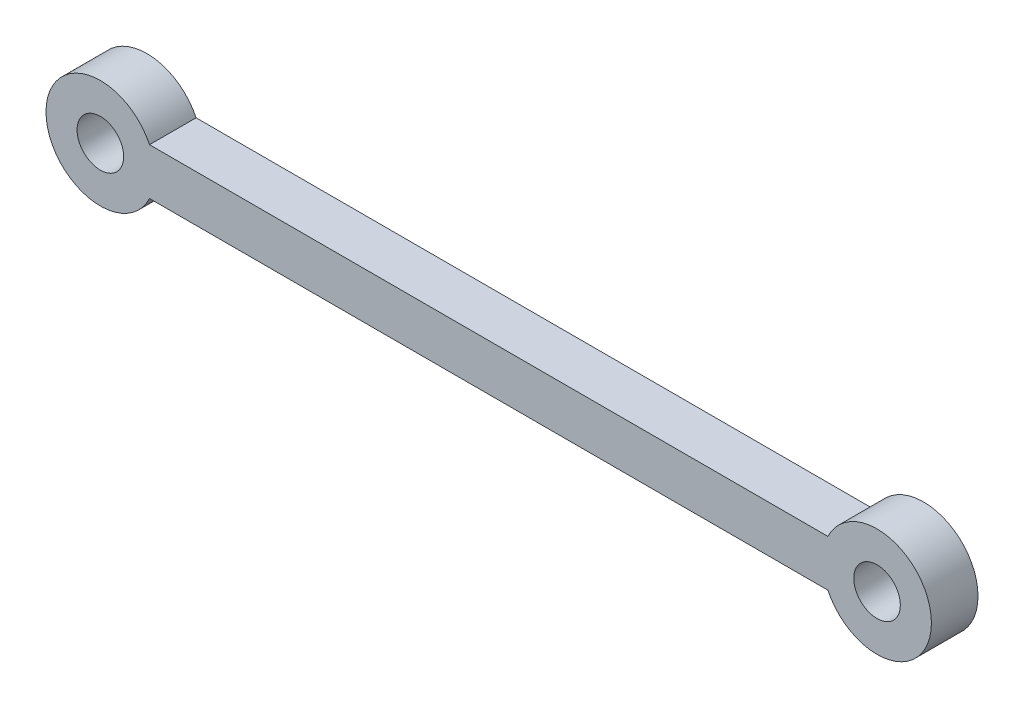
SolidWorks part; units mm, degrees
material "普通碳钢"
ref_plane "前视" through (0, 0, 0) normal (0, 0, 1) x (1, 0, 0)
ref_plane "上视" through (0, 0, 0) normal (0, 1, 0) x (1, 0, 0)
ref_plane "右视" through (0, 0, 0) normal (1, 0, 0) x (0, 0, -1)
sketch "草图1" plane through (0, 0, 0) normal (0, 0, 1) x (1, 0, 0)
  line L0 (0, 0) -> (50, 0) construction
  line L1 (3.1623, 1.5) -> (46.8377, 1.5)
  line L2 (3.1623, -1.5) -> (46.8377, -1.5)
  arc A0 (3.1623, 1.5) -> (3.1623, -1.5) centre (0, 0) ccw
  arc A1 (46.8377, -1.5) -> (46.8377, 1.5) centre (50, 0) ccw
  circle A2 centre (0, 0) radius 1.5
  circle A3 centre (50, 0) radius 1.5
  dimension "D1" = 7
  dimension "D4" = 3
  dimension "D2" = 3
  dimension "D3" = 50
extrude "凸台-拉伸1" add sketch "草图1" along normal blind 3
